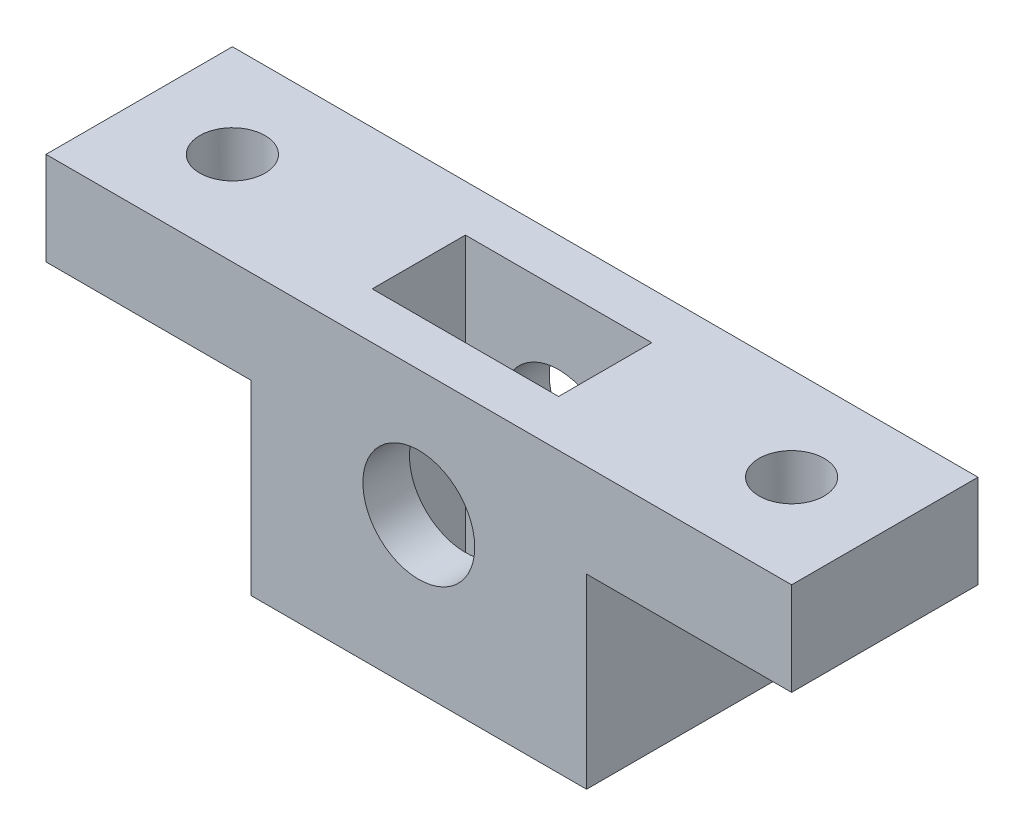
SolidWorks part; units mm, degrees
ref_plane "Plano frontal" through (0, 0, 0) normal (0, 0, 1) x (1, 0, 0)
ref_plane "Plano superior" through (0, 0, 0) normal (0, 1, 0) x (1, 0, 0)
ref_plane "Plano direito" through (0, 0, 0) normal (1, 0, 0) x (0, 0, -1)
sketch "Esboço1" plane through (0, 0, 0) normal (0, 0, 1) x (1, 0, 0)
  line L2 (-9, -5) -> (-9, -15)
  line L3 (-9, -15) -> (9, -15)
  line L4 (9, -5) -> (9, -15)
  line L7 (-20, 0) -> (-20, -5)
  line L8 (-20, -5) -> (-9, -5)
  line L9 (0, 0) -> (0, -15) construction
  line L10 (20, 0) -> (20, -5)
  line L11 (-20, 0) -> (20, 0)
  line L12 (20, -5) -> (9, -5)
  circle A0 centre (0, -6.75) radius 3
  point P0 (0, 0)
  point P2 (-21.7307, 0)
  point P4 (0, 0)
  point P16 (0, 0)
  dimension "D5" = 15
  dimension "D6" = 6
  dimension "D3" = 6.75
  dimension "D1" = 40
  dimension "D2" = 18
  dimension "D4" = 5
extrude "Ressalto-extrusão1" add sketch "Esboço1" along normal blind 10
sketch "Esboço2" plane through (0, 0, 0) normal (0, 1, 0) x (1, 0, 0)
  line L0 (0, 0) -> (0, -10) construction
  line L1 (20, -10) -> (-20, -10) construction
  circle A0 centre (-15, -5) radius 1.75
  circle A1 centre (15, -5) radius 1.75
  point P7 (0, 0)
  point P8 (0, -5)
  dimension "D1" = 15
  dimension "D2" = 3.5
extrude "Corte-extrusão1" cut sketch "Esboço2" against normal blind 10
sketch "Esboço3" plane through (0, -15, 0) normal (0, -1, 0) x (1, 0, 0)
  line L0 (0, 10) -> (0, 0) construction
  line L1 (-9, 10) -> (9, 10) construction
  line L2 (-9, 0) -> (9, 0) construction
  line L4 (-5, 7.5) -> (5, 7.5)
  line L5 (-5, 7.5) -> (-5, 2.5)
  line L6 (-5, 2.5) -> (5, 2.5)
  line L7 (5, 7.5) -> (5, 2.5)
  line L8 (-5, 7.5) -> (5, 2.5) construction
  line L9 (-5, 2.5) -> (5, 7.5) construction
  point P6 (0, 5)
  dimension "D1" = 10
  dimension "D2" = 5
extrude "Corte-extrusão2" cut sketch "Esboço3" against normal blind 20
